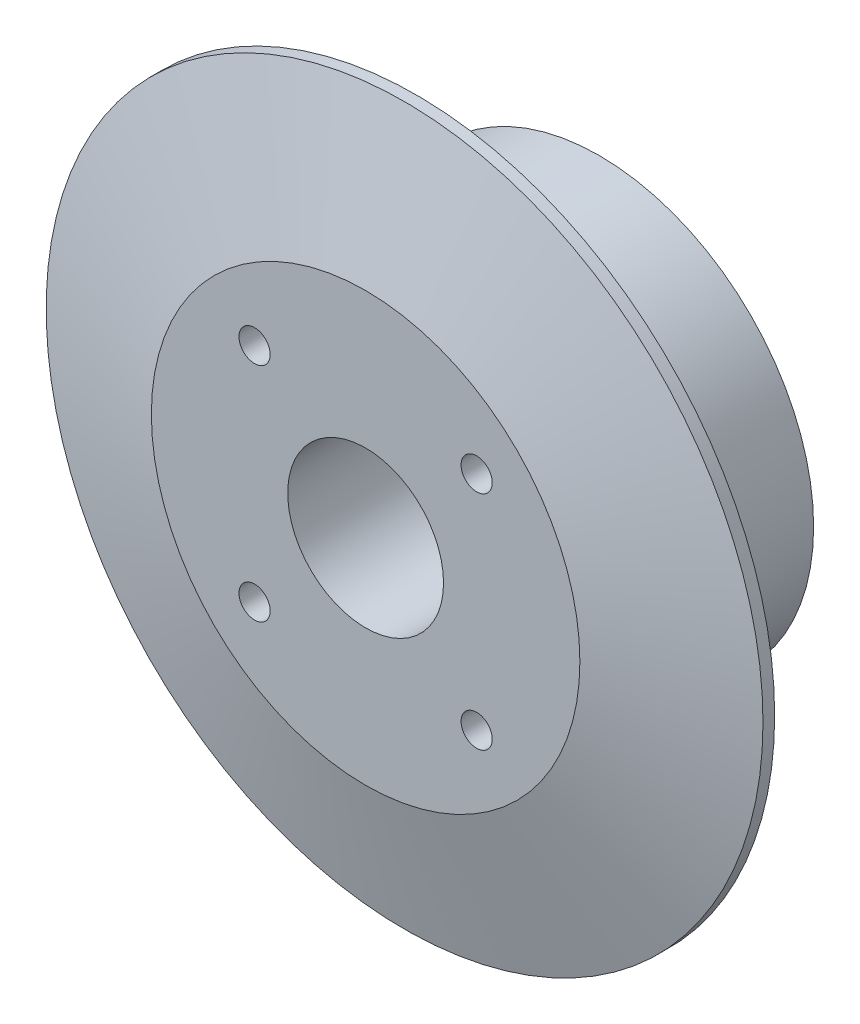
SolidWorks part; units mm, degrees
ref_plane "Front Plane" through (0, 0, 0) normal (0, 0, 1) x (1, 0, 0)
ref_plane "Top Plane" through (0, 0, 0) normal (0, 1, 0) x (1, 0, 0)
ref_plane "Right Plane" through (0, 0, 0) normal (1, 0, 0) x (0, 0, -1)
sketch "Sketch1" plane through (0, 0, 0) normal (1, 0, 0) x (0, 0, -1)
  line L0 (-467.5747, 0) -> (22911.1579, 0) construction
  line L1 (0, 10) -> (0, 27.5)
  line L2 (0, 27.5) -> (5, 46)
  line L3 (5, 46) -> (6.5, 46)
  line L4 (6.5, 46) -> (1.5, 27.5)
  line L5 (1.5, 27.5) -> (30, 27.5)
  line L6 (30, 27.5) -> (30, 10)
  line L7 (30, 10) -> (0, 10)
  dimension "D1" = 55
  dimension "D2" = 92
  dimension "D3" = 1.5
  dimension "D4" = 5
  dimension "D5" = 20
  dimension "D6" = 30
revolve "Revolve1" add sketch "Sketch1" angle 360 about L0
sketch "Sketch2" plane through (0, 0, 0) normal (0, 0, 1) x (1, 0, 0)
  line L1 (14.25, -14.25) -> (-14.25, -14.25) construction
  line L2 (14.25, -14.25) -> (14.25, 14.25) construction
  line L3 (14.25, 14.25) -> (-14.25, 14.25) construction
  line L4 (-14.25, -14.25) -> (-14.25, 14.25) construction
  line L5 (14.25, -14.25) -> (-14.25, 14.25) construction
  line L6 (14.25, 14.25) -> (-14.25, -14.25) construction
  circle A0 centre (-14.25, 14.25) radius 2
  circle A1 centre (14.25, 14.25) radius 2
  circle A2 centre (14.25, -14.25) radius 2
  circle A3 centre (-14.25, -14.25) radius 2
  point P0 (0, 0)
  dimension "D3" = 4
  dimension "D1" = 28.5
  dimension "D2" = 28.5
extrude "Cut-Extrude1" cut sketch "Sketch2" against normal through all
